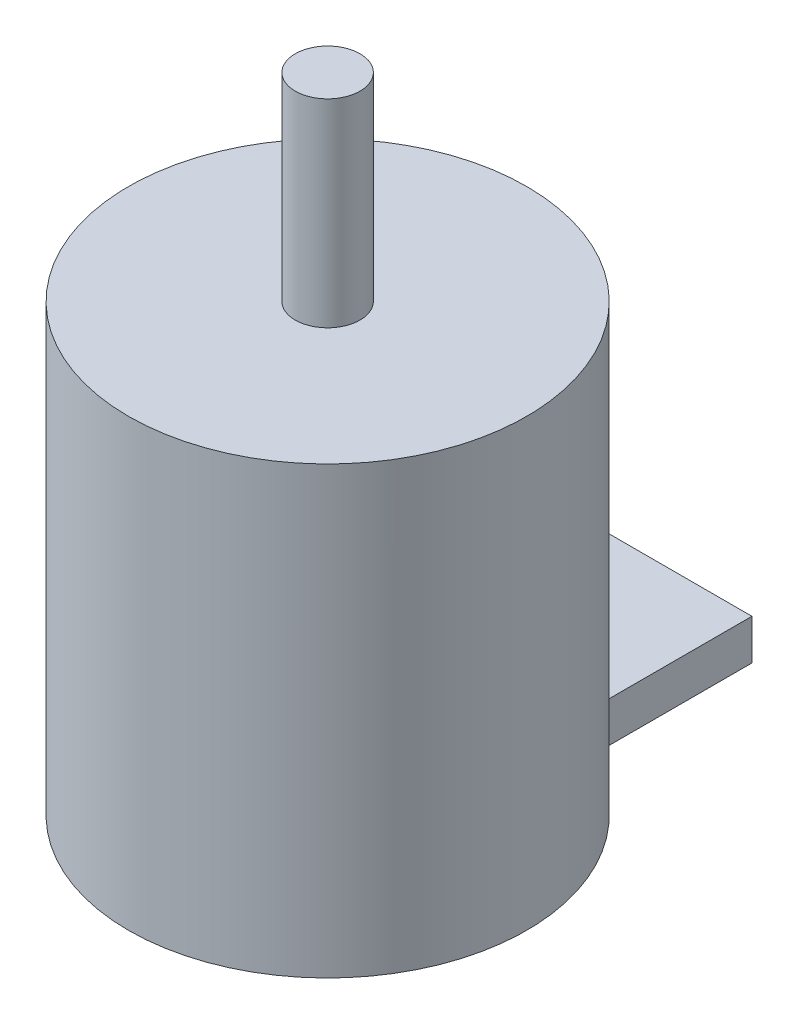
SolidWorks part; units mm, degrees
ref_plane "Front Plane" through (0, 0, 0) normal (0, 0, 1) x (1, 0, 0)
ref_plane "Top Plane" through (0, 0, 0) normal (0, 1, 0) x (1, 0, 0)
ref_plane "Right Plane" through (0, 0, 0) normal (1, 0, 0) x (0, 0, -1)
sketch "Sketch1" plane through (0, 0, 0) normal (0, 1, 0) x (1, 0, 0)
  circle A0 centre (0, 0) radius 24.6
  dimension "D1" = 49.2
extrude "Boss-Extrude1" add sketch "Sketch1" along normal blind 55
sketch "Sketch2" plane through (0, 55, 0) normal (0, 1, 0) x (1, 0, 0)
  circle A0 centre (0, 0) radius 4
  dimension "D1" = 8
extrude "Boss-Extrude2" add sketch "Sketch2" along normal blind 24.5
sketch "Sketch3" plane through (0, 0, 0) normal (0, -1, 0) x (1, 0, 0)
  line L0 (0, 0) -> (0, -45.0413) construction
  line L1 (-9.8984, -22.5207) -> (9.8984, -22.5207)
  line L2 (-9.8984, -22.5207) -> (-9.8984, -42.5207)
  line L3 (-9.8984, -42.5207) -> (9.8984, -42.5207)
  line L4 (9.8984, -22.5207) -> (9.8984, -42.5207)
  circle A0 centre (0, 0) radius 24.6 construction
  point P7 (0, 0)
  point P8 (0, 0)
  point P11 (0, -22.5207)
  dimension "D1" = 20
extrude "Boss-Extrude3" add sketch "Sketch3" against normal blind 5
